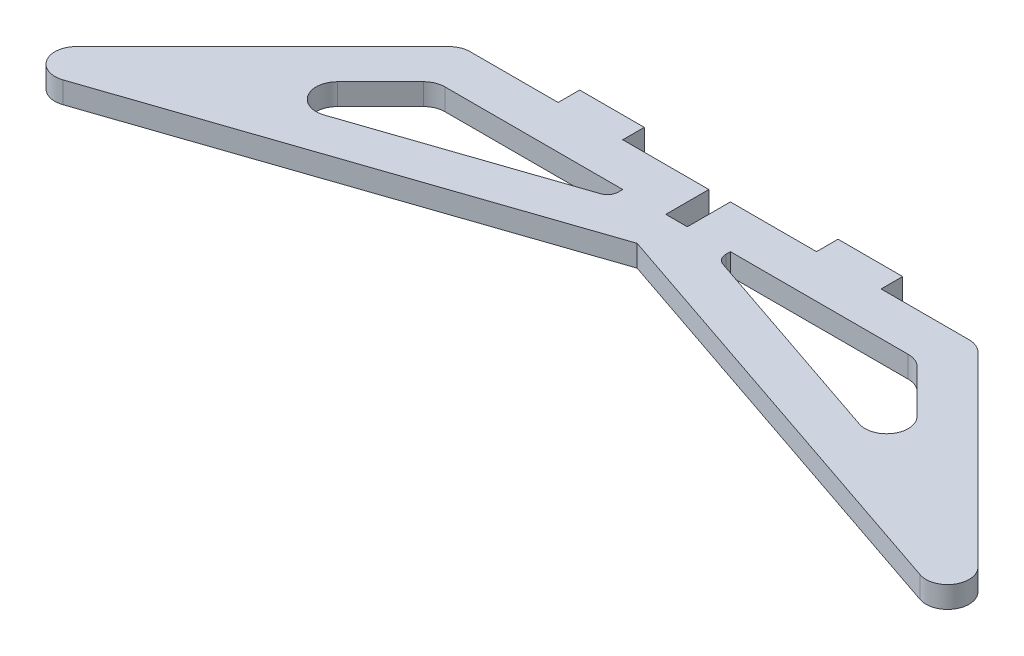
SolidWorks part; units mm, degrees
ref_plane "Front Plane" through (0, 0, 0) normal (0, 0, 1) x (1, 0, 0)
ref_plane "Top Plane" through (0, 0, 0) normal (0, 1, 0) x (1, 0, 0)
ref_plane "Right Plane" through (0, 0, 0) normal (1, 0, 0) x (0, 0, -1)
sketch "Sketch1" plane through (0, 0, 0) normal (0, 1, 0) x (1, 0, 0)
  line L0 (-36.7849, 0) -> (-23.8125, 0)
  line L1 (-1.5875, -6.35) -> (1.5875, -6.35)
  line L2 (-1.5875, -6.35) -> (-1.5875, -12.7) construction
  line L3 (1.5875, -6.35) -> (1.5875, -12.7) construction
  line L4 (14.2875, 3.175) -> (14.2875, 0)
  line L5 (23.8125, 3.175) -> (23.8125, 0)
  line L6 (-14.2875, 3.175) -> (-14.2875, 0)
  line L7 (-23.8125, 3.175) -> (-23.8125, 0)
  line L10 (-23.8125, 38.1) -> (-23.8125, -38.1) construction
  line L11 (-14.2875, 38.1) -> (-14.2875, -38.1) construction
  line L12 (-23.8125, 3.175) -> (-14.2875, 3.175)
  line L13 (-63.2032, -33.6206) -> (-1.5875, -12.7) construction
  line L14 (-39.4529, -18.8505) -> (-9.0146, -8.5157)
  line L15 (63.2032, -33.6206) -> (1.5875, -12.7) construction
  line L16 (14.2875, 38.1) -> (14.2875, -38.1) construction
  line L17 (23.8125, 38.1) -> (23.8125, -38.1) construction
  line L19 (-38.1, -6.35) -> (38.1, -6.35) construction
  line L20 (1.5875, 0) -> (1.5875, -6.35)
  line L21 (-1.5875, 0) -> (-1.5875, -6.35)
  line L22 (-14.2875, 0) -> (-1.5875, 0)
  line L23 (-38.1, 0) -> (38.1, 0) construction
  line L24 (1.5875, 0) -> (14.2875, 0)
  line L25 (-36.3997, -7.2799) -> (-42.7188, -13.599)
  line L26 (-34.1546, -6.35) -> (-7.9375, -6.35)
  line L27 (23.8125, 0) -> (36.7849, 0)
  line L28 (-39.0299, -0.9299) -> (-66.4691, -28.3691)
  line L29 (-63.2032, -33.6206) -> (0, -12.161)
  line L30 (39.4529, -18.8505) -> (9.0146, -8.5157)
  line L31 (63.2032, -33.6206) -> (0, -12.161)
  line L32 (39.0299, -0.9299) -> (66.4691, -28.3691)
  line L33 (36.3997, -7.2799) -> (42.7188, -13.599)
  line L34 (7.9375, -6.35) -> (34.1546, -6.35)
  line L35 (-65.2448, -27.6077) -> (-3.6291, -6.6871) construction
  line L36 (-34.5398, -5.4201) -> (-61.9789, -32.8592) construction
  line L37 (-36.7849, -6.35) -> (-23.8125, -6.35) construction
  line L38 (23.8125, -6.35) -> (36.7849, -6.35) construction
  line L39 (34.5398, -5.4201) -> (61.9789, -32.8592) construction
  line L40 (65.2448, -27.6077) -> (3.6291, -6.6871) construction
  line L41 (-7.9375, -6.35) -> (-7.9375, -7.0125)
  line L42 (7.9375, -6.35) -> (7.9375, -7.0125)
  line L43 (-7.9375, -6.35) -> (-7.9375, -12.7) construction
  line L44 (7.9375, -6.35) -> (7.9375, -12.7) construction
  line L45 (14.2875, 3.175) -> (23.8125, 3.175)
  arc A0 (-36.7849, 0) -> (-39.0299, -0.9299) centre (-36.7849, -3.175) ccw
  arc A1 (39.0299, -0.9299) -> (36.7849, 0) centre (36.7849, -3.175) ccw
  arc A2 (63.2032, -33.6206) -> (66.4691, -28.3691) centre (64.224, -30.6141) ccw
  arc A3 (-66.4691, -28.3691) -> (-63.2032, -33.6206) centre (-64.224, -30.6141) ccw
  arc A4 (39.4529, -18.8505) -> (42.7188, -13.599) centre (40.4737, -15.8441) ccw
  arc A5 (34.1546, -6.35) -> (36.3997, -7.2799) centre (34.1546, -9.525) cw
  arc A6 (-34.1546, -6.35) -> (-36.3997, -7.2799) centre (-34.1546, -9.525) ccw
  arc A7 (-39.4529, -18.8505) -> (-42.7188, -13.599) centre (-40.4737, -15.8441) cw
  arc A8 (9.0146, -8.5157) -> (7.9375, -7.0125) centre (9.525, -7.0125) cw
  arc A9 (-7.9375, -7.0125) -> (-9.0146, -8.5157) centre (-9.525, -7.0125) cw
extrude "Boss-Extrude1" add sketch "Sketch1" along normal blind 3.175
